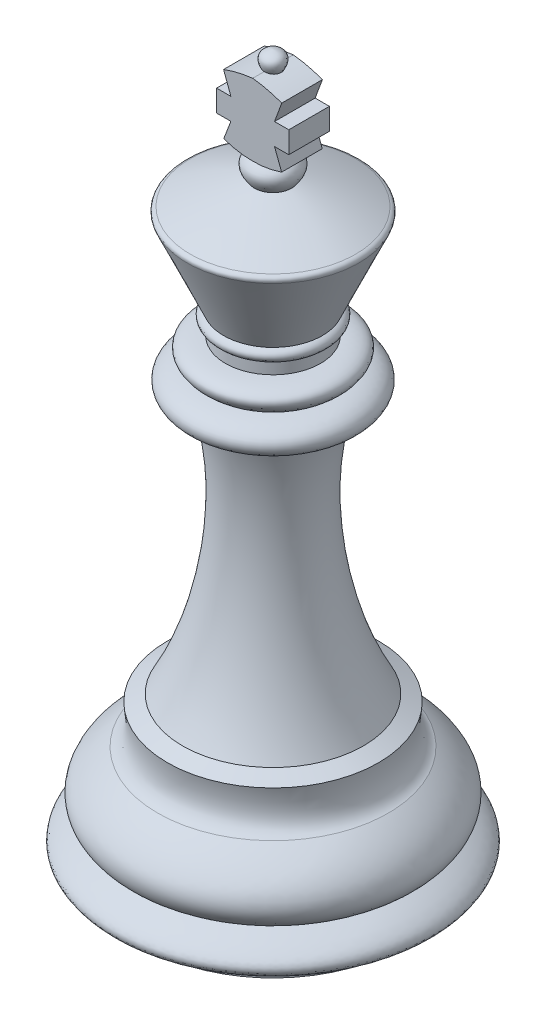
SolidWorks part; units mm, degrees
ref_plane "Front Plane" through (0, 0, 0) normal (0, 0, 1) x (1, 0, 0)
ref_plane "Top Plane" through (0, 0, 0) normal (0, 1, 0) x (1, 0, 0)
ref_plane "Right Plane" through (0, 0, 0) normal (1, 0, 0) x (0, 0, -1)
sketch "Sketch1" plane through (0, 0, 0) normal (0, 0, 1) x (1, 0, 0)
  line L0 (0, 0) -> (157.5346, 0)
  line L2 (0, 0) -> (0, 878.3318)
  line L3 (157.5346, 0) -> (157.5346, 9.8486)
  line L4 (129.8392, 182.8916) -> (111.2355, 191.5128)
  line L5 (73.7047, 510.9414) -> (86.5104, 510.9414)
  line L6 (58.5129, 572.6753) -> (58.5129, 586.8923)
  line L7 (60.7398, 603.4162) -> (105.6852, 703.2905)
  line L8 (9.1705, 857.0684) -> (9.1705, 771.5304)
  line L9 (9.1705, 771.5304) -> (16.9847, 771.5304)
  spline S0 degree 2 poles (157.5346, 9.8486) (170.6911, 10.7592) (179.8711, 18.496) knots 0 0 0 1 1 1
  spline S1 degree 3 poles (179.8711, 18.496) (197.3893, 28.4692) (213.0455, 38.4801) (164.2434, 60.3393) knots 0 0 0 0 1 1 1 1
  spline S2 degree 3 poles (164.2434, 60.3393) (192.2754, 79.4907) (185.4021, 106.9561) (141.8282, 135.192) knots 0 0 0 0 1 1 1 1
  spline S3 degree 2 poles (141.8282, 135.192) (122.5883, 143.7697) (129.8392, 182.8916) knots 0 0 0 1 1 1
  spline S4 degree 3 poles (111.2355, 191.5128) (59.1891, 285.3273) (43.1903, 422.1889) (73.7047, 510.9414) knots 0 0 0 0 1 1 1 1
  spline S5 degree 3 poles (86.5104, 510.9414) (107.2018, 510.6926) (120.0021, 539.6145) (76.2127, 545.389) knots 0 0 0 0 1 1 1 1
  spline S6 degree 3 poles (76.2127, 545.389) (95.4447, 559.9446) (90.5623, 572.5048) (58.5129, 572.6753) knots 0 0 0 0 1 1 1 1
  spline S7 degree 3 poles (58.5129, 586.8923) (68.878, 591.4564) (69.6743, 599.3551) (60.7398, 603.4162) knots 0 0 0 0 1 1 1 1
  spline S8 degree 2 poles (22.8192, 741.5538) (64.1931, 729.008) (101.8362, 710.762) knots 0 0 0 1 1 1
  spline S9 degree 3 poles (105.6852, 703.2905) (107.1803, 706.9109) (105.7824, 709.3509) (101.8362, 710.762) knots 0 0 0 0 1 1 1 1
  spline S10 degree 3 poles (22.8192, 741.5538) (34.2706, 755.5311) (30.6468, 764.5327) (16.9847, 771.5304) knots 0 0 0 0 1 1 1 1
  spline S11 degree 2 poles (0, 878.3318) (20.4046, 875.1472) (9.1705, 857.0684) knots 0 0 0 1 1 1
revolve "Revolve1" add sketch "Sketch1" angle 360 about L2
sketch "Sketch2" plane through (0, 0, 0) normal (0, 0, 1) x (1, 0, 0)
  line L0 (0, 0) -> (0, 878.3318) construction
  line L1 (-35.8076, 851.2855) -> (-26.8495, 827.1391)
  line L2 (-26.8495, 827.1391) -> (-44.4006, 827.1391)
  line L3 (-44.4006, 827.1391) -> (-44.4006, 800.5193)
  line L4 (-44.4006, 800.5193) -> (-26.8495, 800.5193)
  line L5 (-26.8495, 800.5193) -> (-35.625, 777.5971)
  line L6 (16.9847, 771.5304) -> (-16.9847, 771.5304) construction
  line L7 (0, 891.4548) -> (0, 743.1376) construction
  line L8 (26.8495, 800.5193) -> (35.625, 777.5971)
  line L9 (44.4006, 800.5193) -> (26.8495, 800.5193)
  line L10 (44.4006, 827.1391) -> (44.4006, 800.5193)
  line L11 (26.8495, 827.1391) -> (44.4006, 827.1391)
  line L12 (35.8076, 851.2855) -> (26.8495, 827.1391)
  spline S0 degree 2 poles (-35.8076, 851.2855) (-18.2337, 857.8054) (0, 859.7876) knots 0 0 0 1 1 1
  spline S1 degree 2 poles (-35.625, 777.5971) (-17.3706, 771.2869) (0, 771.5304) knots 0 0 0 1 1 1
  spline S2 degree 2 poles (35.625, 777.5971) (17.3706, 771.2869) (0, 771.5304) knots 0 0 0 1 1 1
  spline S3 degree 2 poles (35.8076, 851.2855) (18.2337, 857.8054) (0, 859.7876) knots 0 0 0 1 1 1
extrude "Boss-Extrude1" add sketch "Sketch2" along normal mid plane 50
scale "Scale2" scale about origin uniform scaling yes scale factor 0.5
